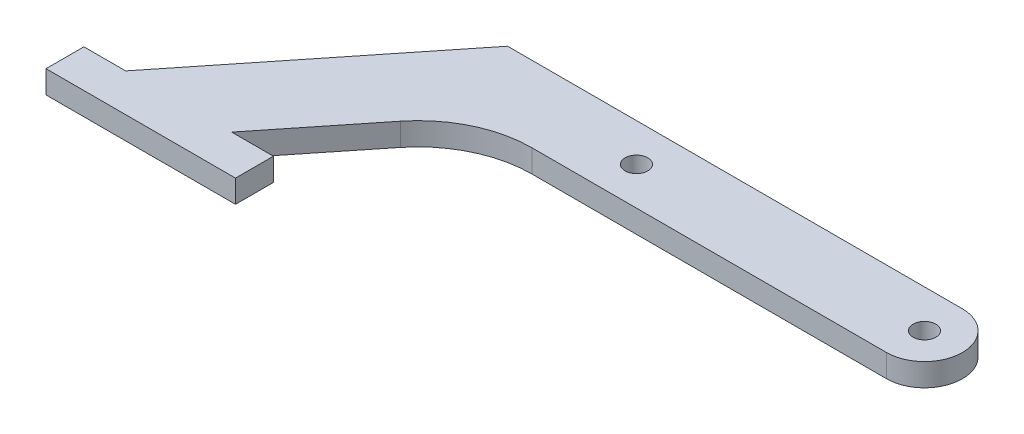
SolidWorks part; units mm, degrees
ref_plane "前视基准面" through (0, 0, 0) normal (0, 0, 1) x (1, 0, 0)
ref_plane "上视基准面" through (0, 0, 0) normal (0, 1, 0) x (1, 0, 0)
ref_plane "右视基准面" through (0, 0, 0) normal (1, 0, 0) x (0, 0, -1)
sketch "草图1" plane through (0, 0, 0) normal (0, 1, 0) x (1, 0, 0)
  line L0 (0, 5) -> (-60, 5)
  line L2 (0, -5) -> (-54, -5)
  line L9 (-60, 5) -> (-82.3717, -23.0157)
  line L10 (-54, -5) -> (-68.3863, -23.0157)
  line L11 (-68.3863, -23.0157) -> (-62.879, -23.0157)
  line L12 (-62.879, -23.0157) -> (-62.879, -28.0157)
  line L13 (-62.879, -28.0157) -> (-87.879, -28.0157)
  line L14 (-87.879, -28.0157) -> (-87.879, -23.0157)
  line L15 (-87.879, -23.0157) -> (-82.3717, -23.0157)
  line L16 (-75.379, -55.7263) -> (-75.379, -0.3051) construction
  line L17 (-30, 5) -> (-30, -5) construction
  line L18 (-51.4058, 0) -> (-8.5942, 0) construction
  circle A0 centre (0, 0) radius 1.5
  arc A1 (0, -5) -> (0, 5) centre (0, 0) ccw
  circle A2 centre (-38, 0) radius 1.5
  point P17 (-75.379, -28.0157)
  point P18 (0, 0)
  point P23 (-30, 0)
  dimension "D1" = 3
  dimension "D2" = 10
  dimension "D7" = 3
  dimension "D3" = 60
  dimension "D4" = 54
  dimension "D5" = 5
  dimension "D6" = 25
  dimension "D8" = 38
extrude "凸台-拉伸1" add sketch "草图1" along normal blind 3
fillet "圆角5" radius 15 1 edges at (-54, 1.5, 5)
